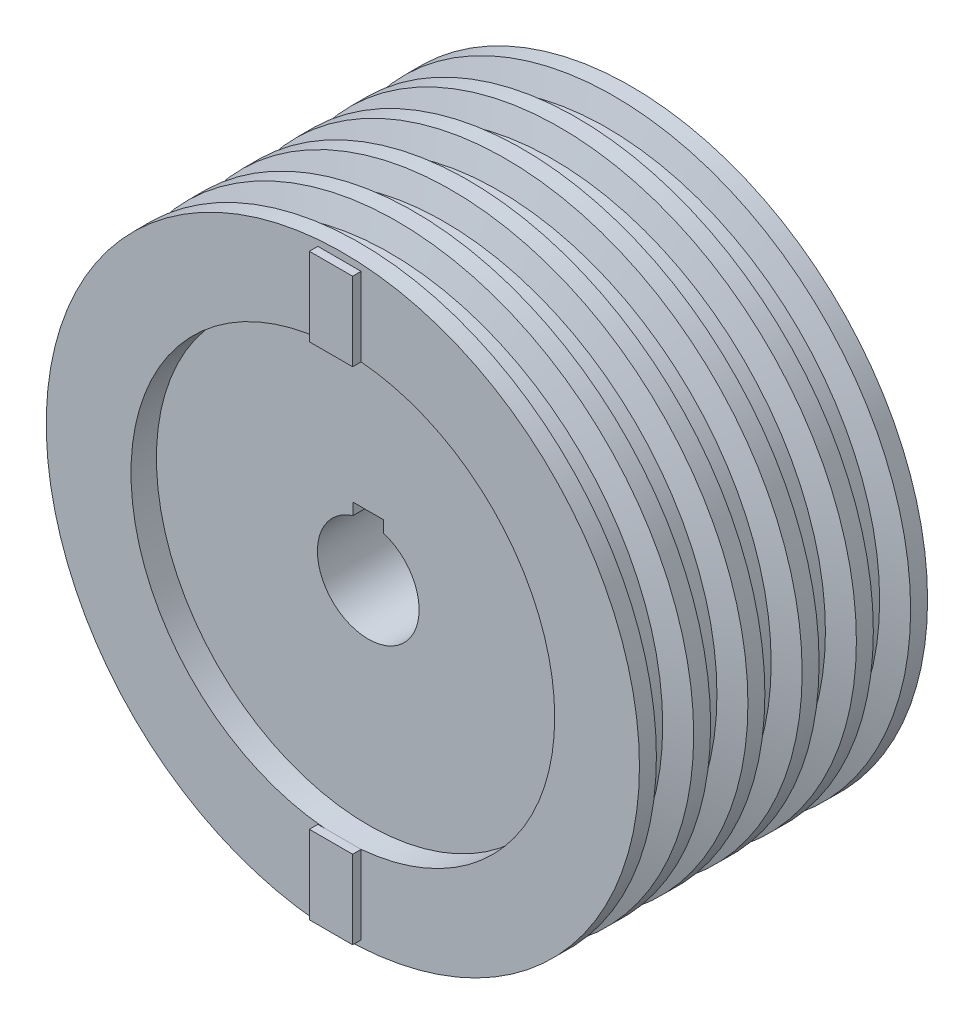
SolidWorks part; units mm, degrees
material "Gray Cast Iron"
ref_plane "Front Plane" through (0, 0, 0) normal (0, 0, 1) x (1, 0, 0)
ref_plane "Top Plane" through (0, 0, 0) normal (0, 1, 0) x (1, 0, 0)
ref_plane "Right Plane" through (0, 0, 0) normal (1, 0, 0) x (0, 0, -1)
sketch "Sketch1" plane through (0, 0, 0) normal (0, 0, 1) x (1, 0, 0)
  circle A0 centre (0, 0) radius 175
  dimension "D1" = 350
extrude "Boss-Extrude1" add sketch "Sketch1" along normal mid plane 170
sketch "Sketch3" plane through (0, 0, 85) normal (0, 0, 1) x (1, 0, 0)
  circle A0 centre (0, 0) radius 30
  dimension "D1" = 60
extrude "Cut-Extrude1" cut sketch "Sketch3" against normal through all
sketch "Sketch4" plane through (0, 0, 85) normal (0, 0, 1) x (1, 0, 0)
  circle A0 centre (0, 0) radius 125
  circle A1 centre (0, 0) radius 30 construction
  circle A2 centre (0, 0) radius 30
  dimension "D1" = 250
extrude "Cut-Extrude2" cut sketch "Sketch4" against normal blind 15
mirror "Mirror1" about plane through (0, 0, 0) normal (0, 0, 1) of "Cut-Extrude2"
sketch "Sketch5" plane through (0, 0, 70) normal (0, 0, 1) x (1, 0, 0)
  line L1 (-9, 24.5) -> (9, 24.5)
  line L2 (-9, 24.5) -> (-9, 35.5)
  line L3 (-9, 35.5) -> (9, 35.5)
  line L4 (9, 24.5) -> (9, 35.5)
  line L5 (-9, 24.5) -> (9, 35.5) construction
  line L6 (-9, 35.5) -> (9, 24.5) construction
  circle A0 centre (0, 0) radius 30 construction
  point P0 (0, 30)
  dimension "D1" = 18
  dimension "D2" = 11
extrude "Cut-Extrude3" cut sketch "Sketch5" against normal through all
sketch "Sketch9" plane through (0, 0, 0) normal (0, 1, 0) x (1, 0, 0)
  line L0 (175, 75) -> (161, 70.7198)
  line L1 (175, -85) -> (175, 85) construction
  line L2 (161, 70.7198) -> (161, 57.2802)
  line L3 (161, 57.2802) -> (175, 53)
  line L4 (175, 53) -> (175, 75)
  line L5 (175, 85) -> (-175, 85) construction
  line L6 (104.62, 48) -> (276.5217, 48) construction
  line L7 (276.5217, 48) -> (276.5217, 16) construction
  line L8 (276.5217, 16) -> (99.1192, 16) construction
  line L9 (99.1192, 16) -> (99.1192, -20.2139) construction
  line L10 (99.1192, -20.2139) -> (276.5217, -20.2139) construction
  line L11 (276.5217, -20.2139) -> (276.5217, -48) construction
  line L12 (276.5217, -48) -> (99.0813, -48) construction
  line L13 (175, 43) -> (175, 21)
  line L14 (161, 38.7198) -> (175, 43)
  line L15 (161, 25.2802) -> (161, 38.7198)
  line L16 (175, 21) -> (161, 25.2802)
  line L17 (175, 11) -> (161, 6.7198)
  line L18 (161, 6.7198) -> (161, -6.7198)
  line L19 (161, -6.7198) -> (175, -11)
  line L20 (175, -11) -> (175, 11)
  line L21 (175, -21) -> (175, -43)
  line L22 (161, -25.2802) -> (175, -21)
  line L23 (161, -38.7198) -> (161, -25.2802)
  line L24 (175, -43) -> (161, -38.7198)
  line L25 (175, -53) -> (161, -57.2802)
  line L26 (161, -57.2802) -> (161, -70.7198)
  line L27 (161, -70.7198) -> (175, -75)
  line L28 (175, -75) -> (175, -53)
  line L29 (0, 0) -> (0, 124.531) construction
  dimension "D1" = 10
  dimension "D2" = 22
  dimension "D3" = 14
  dimension "D4" = 73
  dimension "D5" = 73
  dimension "D6" = 5
  dimension "D7" = 5
  dimension "D8" = 5
revolve "Cut-Revolve2" cut sketch "Sketch9" angle 360 about L29
sketch "Sketch10" plane through (0, 0, 85) normal (0, 0, 1) x (1, 0, 0)
  line L0 (0, 0) -> (293.4495, 0) construction
  line L1 (-14.7462, 170.8102) -> (10.7654, 170.8102)
  line L2 (-14.7462, 170.8102) -> (-14.7462, 124.5356)
  line L3 (-14.7462, 124.5356) -> (10.7654, 124.5356)
  line L4 (10.7654, 170.8102) -> (10.7654, 124.5356)
  line L5 (10.7654, -170.8102) -> (10.7654, -124.5356)
  line L6 (-14.7462, -124.5356) -> (10.7654, -124.5356)
  line L7 (-14.7462, -170.8102) -> (-14.7462, -124.5356)
  line L8 (-14.7462, -170.8102) -> (10.7654, -170.8102)
  circle A0 centre (0, 0) radius 125 construction
extrude "Boss-Extrude2" add sketch "Sketch10" along normal blind 5
